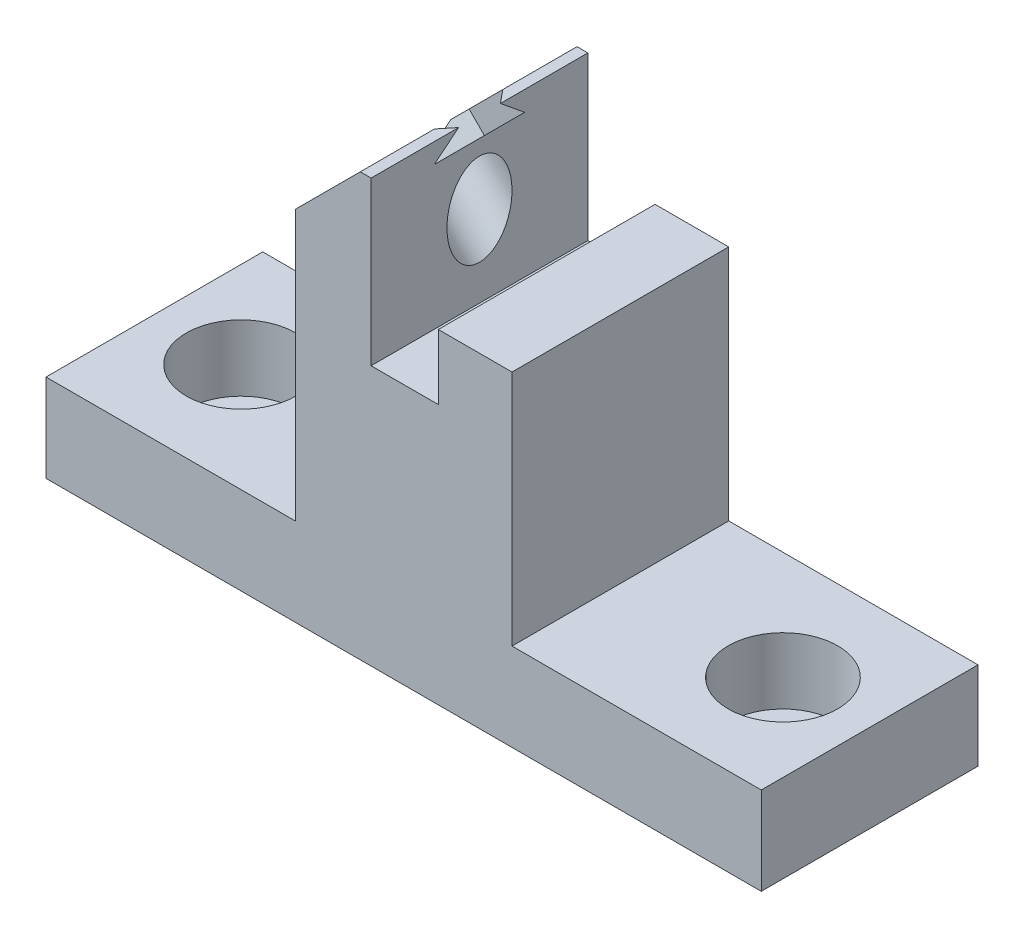
SolidWorks part; units mm, degrees
ref_plane "Front Plane" through (0, 0, 0) normal (0, 0, 1) x (1, 0, 0)
ref_plane "Top Plane" through (0, 0, 0) normal (0, 1, 0) x (1, 0, 0)
ref_plane "Right Plane" through (0, 0, 0) normal (1, 0, 0) x (0, 0, -1)
sketch "Sketch1" plane through (0, 0, 0) normal (0, 1, 0) x (1, 0, 0)
  line L1 (-10, -10) -> (10, -10)
  line L2 (-10, -10) -> (-10, 10)
  line L3 (-10, 10) -> (10, 10)
  line L4 (10, -10) -> (10, 10)
  line L5 (-10, -10) -> (10, 10) construction
  line L6 (-10, 10) -> (10, -10) construction
  point P0 (0, 0)
extrude "Boss-Extrude1" add sketch "Sketch1" along normal blind 6
sketch "Sketch2" plane through (0, 6, 0) normal (0, 1, 0) x (1, 0, 0)
  line L2 (-10, -10) -> (10, -10) construction
  line L3 (3.2, -10) -> (10, -10)
  line L4 (3.2, -10) -> (3.2, 10)
  line L5 (3.2, 10) -> (10, 10)
  line L6 (10, -10) -> (10, 10)
extrude "Boss-Extrude2" add sketch "Sketch2" along normal blind 6
sketch "Sketch3" plane through (0, 6, 0) normal (0, 1, 0) x (1, 0, 0)
  line L0 (-10, 0) -> (-3, 0) construction
  line L1 (-10, 10) -> (-10, -10) construction
  line L2 (3.2, 10) -> (-10, 10) construction
  line L3 (-10, -10) -> (-3, -10)
  line L4 (-10, -10) -> (-10, 10)
  line L5 (-10, 10) -> (-3, 10)
  line L6 (-3, -10) -> (-3, 10)
extrude "Boss-Extrude3" add sketch "Sketch3" along normal blind 15
chamfer "Chamfer1" distance 6 angle 45 1 edges at (-10, 21, 0)
sketch "Sketch4" plane through (-12.5, 12.5, 0) normal (-0.7071, 0.7071, 0) x (0, 0, 1)
  line L0 (0, 3.5355) -> (0, 5.4132) construction
  line L1 (10, 3.5355) -> (-10, 3.5355) construction
  line L2 (0, 5.4132) -> (0, 7.4325) construction
  circle A0 centre (0, 7.4325) radius 3
extrude "Cut-Extrude1" cut sketch "Sketch4" against normal blind 10 contours A0
sketch "Sketch5" plane through (0, 0, 0) normal (0, -1, 0) x (1, 0, 0)
  line L1 (10, -10) -> (-10, -10)
  line L2 (10, -10) -> (10, 10)
  line L3 (10, 10) -> (-10, 10)
  line L4 (-10, -10) -> (-10, 10)
  line L5 (10, -10) -> (-10, 10) construction
  line L6 (10, 10) -> (-10, -10) construction
  point P0 (0, 0)
extrude "Boss-Extrude4" add sketch "Sketch5" along normal blind 18
sketch "Sketch6" plane through (-12.5, 12.5, 0) normal (-0.7071, 0.7071, 0) x (0, 0, 1)
  line L1 (0, 13.8411) -> (-5.55, 10.6368)
  line L2 (-5.55, 10.6368) -> (-5.55, 4.2282)
  line L3 (-5.55, 4.2282) -> (0, 1.0239)
  line L4 (0, 1.0239) -> (5.55, 4.2282)
  line L5 (5.55, 4.2282) -> (5.55, 10.6368)
  line L6 (5.55, 10.6368) -> (0, 13.8411)
  circle A0 centre (0, 7.4325) radius 5.55 construction
extrude "Cut-Extrude2" cut sketch "Sketch6" against normal blind 2 contours L1 L2 L3 L4 L5 L6
sketch "Sketch9" plane through (10, 0, 0) normal (1, 0, 0) x (0, 0, -1)
  line L0 (10, 12) -> (10, -18) construction
  line L1 (-10, -18) -> (10, -18)
  line L2 (-10, -18) -> (-10, -9.9)
  line L3 (-10, -9.9) -> (10, -9.9)
  line L4 (10, -18) -> (10, -9.9)
extrude "Boss-Extrude5" add sketch "Sketch9" along normal blind 23
sketch "Sketch10" plane through (0, -18, 0) normal (0, -1, 0) x (1, 0, 0)
  line L0 (0, 0) -> (25, 0) construction
  circle A0 centre (25, 0) radius 3
extrude "Cut-Extrude5" cut sketch "Sketch10" against normal up to next
sketch "Sketch11" plane through (0, -9.9, 0) normal (0, 1, 0) x (1, 0, 0)
  circle A0 centre (25, 0) radius 5.05
extrude "Cut-Extrude6" cut sketch "Sketch11" against normal blind 6.1
ref_plane "Plane1" through (0, 0, 0) normal (1, 0, 0) x (0, 0, -1)
mirror "Mirror1" about plane through (0, 0, 0) normal (1, 0, 0) of "Cut-Extrude5", "Cut-Extrude6", "Boss-Extrude5"
